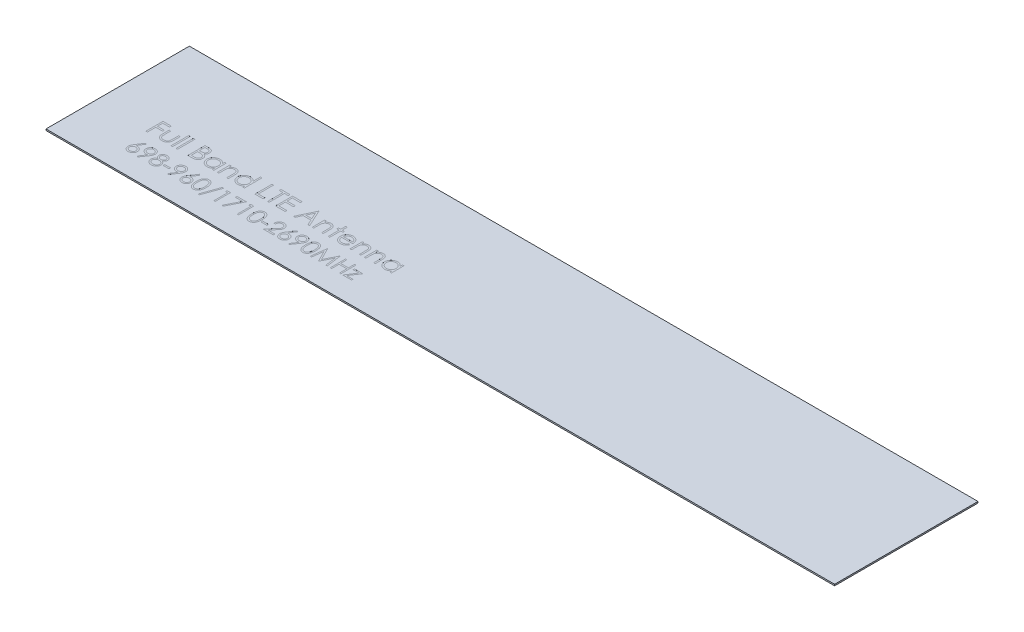
SolidWorks part; units mm, degrees
ref_plane "Ön Düzlem" through (0, 0, 0) normal (0, 0, 1) x (1, 0, 0)
ref_plane "Üst Düzlem" through (0, 0, 0) normal (0, 1, 0) x (1, 0, 0)
ref_plane "Sağ Düzlem" through (0, 0, 0) normal (1, 0, 0) x (0, 0, -1)
sketch "Çizim1" plane through (0, 0, 0) normal (0, 1, 0) x (1, 0, 0)
  line L1 (-55, -10) -> (55, -10)
  line L2 (-55, -10) -> (-55, 10)
  line L3 (-55, 10) -> (55, 10)
  line L4 (55, -10) -> (55, 10)
  line L5 (-55, -10) -> (55, 10) construction
  line L6 (-55, 10) -> (55, -10) construction
  point P0 (0, 0)
  dimension "D1" = 110
  dimension "D2" = 20
extrude "Yükseklik-Ekstrüzyon1" add sketch "Çizim1" along normal blind 0.2
sketch "Çizim2" plane through (0, 0.2, 0) normal (0, 1, 0) x (1, 0, 0)
  line L0 (-48.0644, -3.303) -> (-2.6196, -3.303) construction
  line L1 (-47.3811, -6.9477) -> (-4.6698, -6.9477) construction
  line L2 (-55, -10) -> (55, -10) construction
  text T0 "Full Band LTE Antenna" font "Century Gothic" height in points 9
  text T1 "698-960/1710-2690MHz\r\n" font "Century Gothic" height in points 8
  point P5 (-43.1669, -6.7199)
  point P6 (-4.6698, -6.8338)
  point P7 (-47.3811, -6.9477)
  point P10 (-47.3811, -2.9613)
  point P11 (-48.0644, -3.303)
extrude "Kes-Ekstrüzyon1" cut sketch "Çizim2" against normal blind 0.001
